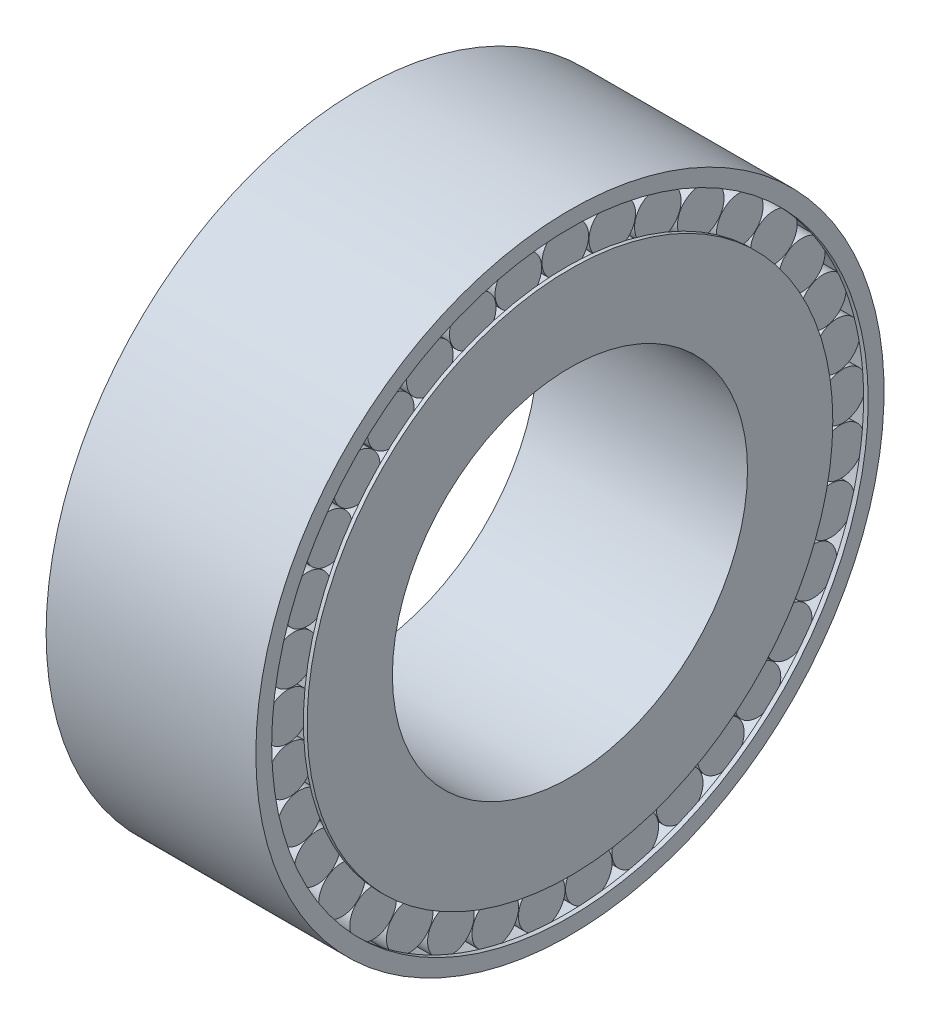
SolidWorks part; units mm, degrees
material "AISI 304"
ref_plane "前视" through (0, 0, 0) normal (0, 0, 1) x (1, 0, 0)
ref_plane "上视" through (0, 0, 0) normal (0, 1, 0) x (1, 0, 0)
ref_plane "右视" through (0, 0, 0) normal (1, 0, 0) x (0, 0, -1)
sketch "草图1" plane through (0, 0, 0) normal (0, 0, 1) x (1, 0, 0)
  line L0 (0, 0) -> (124.2372, 0) construction
  line L2 (0, 67.4) -> (45, 67.4)
  line L3 (0, 67.4) -> (0, 64)
  line L4 (0, 64) -> (1, 64)
  line L5 (1, 64) -> (1, 64.7)
  line L6 (1, 64.7) -> (44, 64.7)
  line L7 (44, 64.7) -> (44, 64)
  line L8 (44, 64) -> (45, 64)
  line L9 (45, 64) -> (45, 67.4)
  line L10 (22.5, 64.7) -> (22.5, 0) construction
  point P15 (16.7245, 0)
  dimension "D1" = 2.7
  dimension "D2" = 134.8
  dimension "D3" = 45
  dimension "D4" = 1
  dimension "D5" = 3.4
revolve "旋转1" add sketch "草图1" angle 360 about L0
sketch "草图3" plane through (0, 0, 0) normal (0, 0, 1) x (1, 0, 0)
  line L0 (1, -64.7) -> (1, 64.7) construction
  line L1 (1, 64.6) -> (20, 64.6)
  line L2 (1, 64.6) -> (1, 59.6)
  line L3 (1, 59.6) -> (20, 59.6)
  line L4 (20, 64.6) -> (20, 59.6)
  line L5 (22.5, 67.4) -> (22.5, -67.4) construction
  line L6 (45, 67.4) -> (0, 67.4) construction
  line L7 (0, -67.4) -> (45, -67.4) construction
  line L8 (44, 64.7) -> (1, 64.7) construction
  line L9 (25, 64.6) -> (25, 59.6)
  line L10 (44, 59.6) -> (25, 59.6)
  line L11 (44, 64.6) -> (44, 59.6)
  line L12 (44, 64.6) -> (25, 64.6)
  dimension "D1" = 5
  dimension "D2" = 0.1
  dimension "D3" = 5
revolve "旋转3" add sketch "草图3" angle 360 about L10
sketch "草图5" plane through (0, 0, 0) normal (0, 0, 1) x (1, 0, 0)
  line L1 (45, -67.4) -> (45, 67.4) construction
  line L8 (0, 38.1) -> (45, 38.1)
  line L12 (0.8, 54.4) -> (20.2, 54.4)
  line L13 (20.2, 54.4) -> (20.2, 55.9)
  line L14 (20.2, 55.9) -> (24.8, 55.9)
  line L15 (24.8, 55.9) -> (24.8, 54.4)
  line L16 (24.8, 54.4) -> (44.2, 54.4)
  line L17 (44, 64.7) -> (44, -64.7) construction
  line L19 (25, 54.6) -> (44, 54.6) construction
  line L20 (20, 54.6) -> (20, 64.6) construction
  line L21 (45, 56.4) -> (45, 38.1)
  line L23 (44.2, 54.4) -> (44.2, 56.4)
  line L24 (44.2, 56.4) -> (45, 56.4)
  line L25 (22.5, 67.4) -> (22.5, 38.1) construction
  line L27 (45, 67.4) -> (0, 67.4) construction
  line L28 (0.8, 54.4) -> (0.8, 56.4)
  line L29 (0.8, 56.4) -> (0, 56.4)
  line L30 (0, 56.4) -> (0, 38.1)
  point P2 (0.785, 54.4)
  point P7 (1, 54.4)
  point P29 (0.0342, 38.1)
  dimension "D1" = 0.2
  dimension "D2" = 38.1
  dimension "D3" = 1.5
  dimension "D4" = 0.2
  dimension "D5" = 0.2
  dimension "D6" = 2
revolve "旋转6" add sketch "草图5" angle 360 about axis through (0, 0, 0) along (-1, 0, 0)
pattern_circular "阵列(圆周)1" count 37 over 360 about axis through (0, 0, 0) along (1, 0, 0) of "旋转3"
